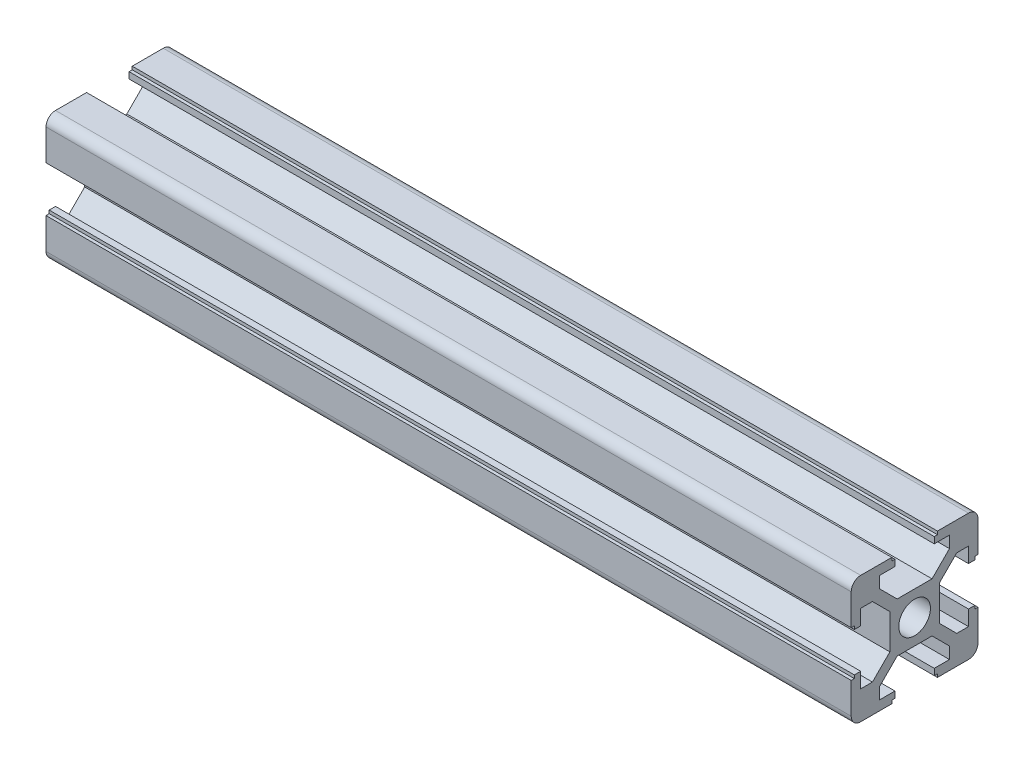
SolidWorks part; units mm, degrees
ref_plane "前视基准面" through (0, 0, 0) normal (0, 0, 1) x (1, 0, 0)
ref_plane "上视基准面" through (0, 0, 0) normal (0, 1, 0) x (1, 0, 0)
ref_plane "右视基准面" through (0, 0, 0) normal (1, 0, 0) x (0, 0, -1)
sketch "草图1" plane through (0, 0, 0) normal (0, 1, 0) x (1, 0, 0)
  line L0 (0, 0) -> (127, 0)
  dimension "D1" = 127
other "铝型材 20 X 20 X R1.5(1)"
ref_plane "基准面1" through (0, 0, 0) normal (1, 0, 0) x (0, 0, -1)
sketch "Sketch1" plane through (0, 0, 0) normal (1, 0, 0) x (0, 0, -1)
  line L0 (-3.6, 10) -> (-3.6, 9.5)
  line L1 (-3.6, 9.5) -> (-3.1, 9.5)
  line L2 (-3.1, 9.5) -> (-3.1, 8.5)
  line L3 (-3.1, 8.5) -> (-5.5, 8.5)
  line L4 (-8.5, -10) -> (-3.6, -10)
  line L5 (-10, -8.5) -> (-10, -3.6)
  line L6 (8.5, 10) -> (3.6, 10)
  line L7 (10, 8.5) -> (10, 3.6)
  line L8 (0, 14.8756) -> (0, 0) construction
  line L9 (0, 0) -> (14.1675, 0) construction
  line L10 (-5.5, 8.5) -> (-5.5, 6.65)
  line L11 (-5.5, 6.65) -> (-2.75, 3.9)
  line L12 (-2.75, 3.9) -> (2.75, 3.9)
  line L13 (5.5, 6.65) -> (2.75, 3.9)
  line L14 (5.5, 8.5) -> (5.5, 6.65)
  line L15 (3.1, 8.5) -> (5.5, 8.5)
  line L16 (3.1, 9.5) -> (3.1, 8.5)
  line L17 (3.6, 9.5) -> (3.1, 9.5)
  line L18 (3.6, 10) -> (3.6, 9.5)
  line L19 (-3.6, 10) -> (-8.5, 10)
  line L20 (10, 3.6) -> (9.5, 3.6)
  line L21 (9.5, 3.6) -> (9.5, 3.1)
  line L22 (9.5, 3.1) -> (8.5, 3.1)
  line L23 (8.5, 3.1) -> (8.5, 5.5)
  line L24 (8.5, 5.5) -> (6.65, 5.5)
  line L25 (6.65, 5.5) -> (3.9, 2.75)
  line L26 (3.9, 2.75) -> (3.9, -2.75)
  line L27 (6.65, -5.5) -> (3.9, -2.75)
  line L28 (8.5, -5.5) -> (6.65, -5.5)
  line L29 (8.5, -3.1) -> (8.5, -5.5)
  line L30 (9.5, -3.1) -> (8.5, -3.1)
  line L31 (9.5, -3.6) -> (9.5, -3.1)
  line L32 (10, -3.6) -> (9.5, -3.6)
  line L33 (3.6, -10) -> (3.6, -9.5)
  line L34 (3.6, -9.5) -> (3.1, -9.5)
  line L35 (3.1, -9.5) -> (3.1, -8.5)
  line L36 (3.1, -8.5) -> (5.5, -8.5)
  line L37 (5.5, -8.5) -> (5.5, -6.65)
  line L38 (5.5, -6.65) -> (2.75, -3.9)
  line L39 (2.75, -3.9) -> (-2.75, -3.9)
  line L40 (-5.5, -6.65) -> (-2.75, -3.9)
  line L41 (-5.5, -8.5) -> (-5.5, -6.65)
  line L42 (-3.1, -8.5) -> (-5.5, -8.5)
  line L43 (-3.1, -9.5) -> (-3.1, -8.5)
  line L44 (-3.6, -9.5) -> (-3.1, -9.5)
  line L45 (-3.6, -10) -> (-3.6, -9.5)
  line L46 (-10, -3.6) -> (-9.5, -3.6)
  line L47 (-9.5, -3.6) -> (-9.5, -3.1)
  line L48 (-9.5, -3.1) -> (-8.5, -3.1)
  line L49 (-8.5, -3.1) -> (-8.5, -5.5)
  line L50 (-8.5, -5.5) -> (-6.65, -5.5)
  line L51 (-6.65, -5.5) -> (-3.9, -2.75)
  line L52 (-3.9, -2.75) -> (-3.9, 2.75)
  line L53 (-6.65, 5.5) -> (-3.9, 2.75)
  line L54 (-8.5, 5.5) -> (-6.65, 5.5)
  line L55 (-8.5, 3.1) -> (-8.5, 5.5)
  line L56 (-9.5, 3.1) -> (-8.5, 3.1)
  line L57 (-9.5, 3.6) -> (-9.5, 3.1)
  line L58 (-10, 3.6) -> (-9.5, 3.6)
  line L59 (3.6, -10) -> (8.5, -10)
  line L60 (-10, 3.6) -> (-10, 8.5)
  line L61 (10, -3.6) -> (10, -8.5)
  circle A0 centre (0, 0) radius 2.5
  arc A1 (-10, 8.5) -> (-8.5, 10) centre (-8.5, 8.5) cw
  arc A2 (10, 8.5) -> (8.5, 10) centre (8.5, 8.5) ccw
  arc A3 (-8.5, -10) -> (-10, -8.5) centre (-8.5, -8.5) cw
  arc A4 (8.5, -10) -> (10, -8.5) centre (8.5, -8.5) ccw
  point P0 (-10, 0)
  point P1 (10, 0)
  point P2 (0, 10)
  point P3 (0, -10)
  point P4 (0, 0)
  point P5 (-10, -10)
  point P6 (10, -10)
  point P7 (10, 10)
  point P8 (-10, 10)
  point P13 (0, 0)
  point P36 (-10, 10)
  point P39 (10, 10)
  dimension "D1" = 11
  dimension "D2" = 20
  dimension "D3" = 6.2
  dimension "D4" = 7.2
  dimension "D5" = 6.1
  dimension "D6" = 5
  dimension "D7" = 1.5
  dimension "D8" = 45
  dimension "D9" = 0.5
  dimension "D10" = 1
  dimension "D11" = 5.5
